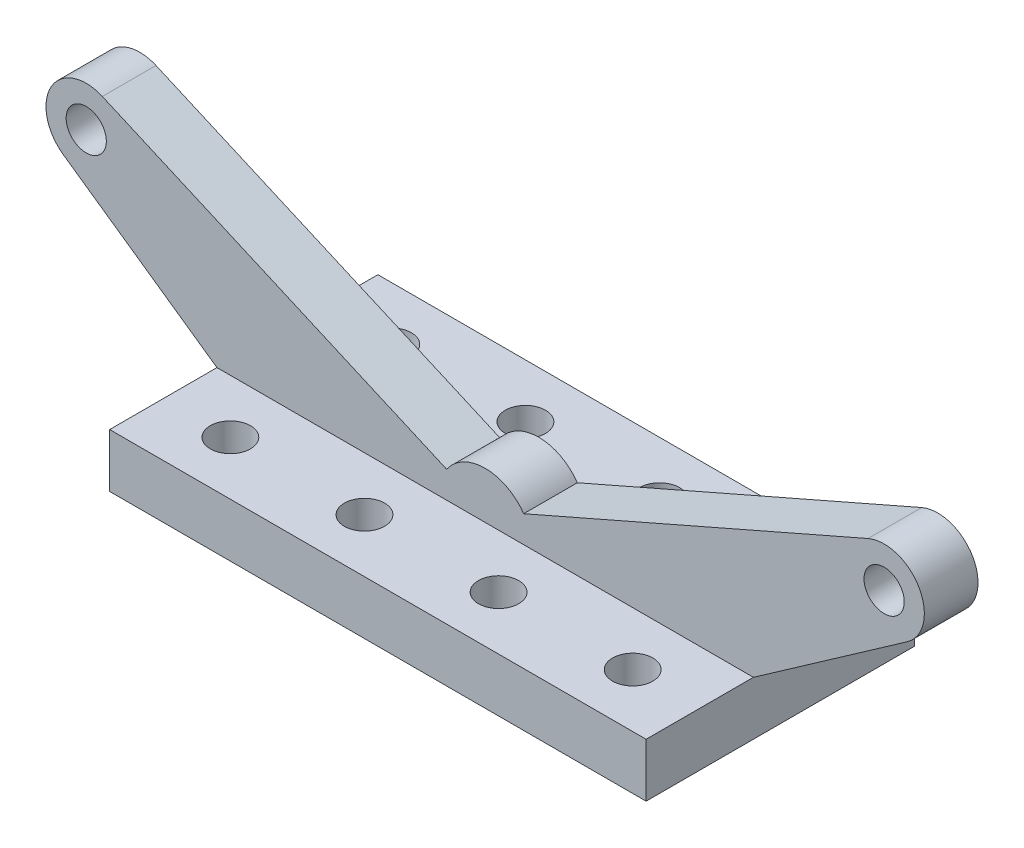
SolidWorks part; units mm, degrees
ref_plane "Front Plane" through (0, 0, 0) normal (0, 0, 1) x (1, 0, 0)
ref_plane "Top Plane" through (0, 0, 0) normal (0, 1, 0) x (1, 0, 0)
ref_plane "Right Plane" through (0, 0, 0) normal (1, 0, 0) x (0, 0, -1)
sketch "Sketch1" plane through (0, 0, 0) normal (0, 1, 0) x (1, 0, 0)
  line L0 (0, 0) -> (-100, 0) construction
  line L1 (-100, -50) -> (100, -50)
  line L2 (-100, -50) -> (-100, 50)
  line L3 (-100, 50) -> (100, 50)
  line L4 (100, -50) -> (100, 50)
  line L5 (-100, -50) -> (100, 50) construction
  line L6 (-100, 50) -> (100, -50) construction
  circle A0 centre (-75, 30) radius 7.5
  circle A1 centre (-75, -30) radius 7.5
  circle A2 centre (-25, 30) radius 7.5
  circle A3 centre (-25, -30) radius 7.5
  circle A4 centre (25, 30) radius 7.5
  circle A5 centre (25, -30) radius 7.5
  circle A6 centre (75, 30) radius 7.5
  circle A7 centre (75, -30) radius 7.5
  point P0 (0, 0)
  dimension "D3" = 15
  dimension "D5" = 60
  dimension "D6" = 4
  dimension "D7" = 50
  dimension "D1" = 200
  dimension "D2" = 100
  dimension "D4" = 25
extrude "Boss-Extrude1" add sketch "Sketch1" along normal blind 20
sketch "Sketch2" plane through (0, 0, 0) normal (0, 0, 1) x (1, 0, 0)
  line L0 (-100, 20) -> (-157.3406, 60.1504)
  line L1 (-100, 20) -> (100, 20) construction
  line L2 (0, 0) -> (0, 87.6863) construction
  line L3 (-157.3406, 60.1504) -> (-138.0598, 87.6863) construction
  line L4 (-142.7228, 86.1792) -> (-14.3614, 30)
  line L5 (157.3406, 60.1504) -> (138.0598, 87.6863) construction
  line L6 (142.7228, 86.1792) -> (14.3614, 30)
  line L7 (100, 20) -> (157.3406, 60.1504)
  line L8 (-100, 20) -> (100, 20)
  arc A0 (-142.7228, 86.1792) -> (-157.3406, 60.1504) centre (-148.737, 72.4376) ccw
  arc A1 (14.3614, 30) -> (-14.3614, 30) centre (0, 20) ccw
  circle A2 centre (-148.737, 72.4376) radius 7.5
  circle A3 centre (148.737, 72.4376) radius 7.5
  arc A4 (142.7228, 86.1792) -> (157.3406, 60.1504) centre (148.737, 72.4376) cw
  point P9 (-14.0639, 30.4143)
  dimension "D3" = 30
  dimension "D4" = 35
  dimension "D5" = 15
  dimension "D1" = 70
  dimension "D2" = 145
  dimension "D6" = 10
extrude "Boss-Extrude2" add sketch "Sketch2" along normal mid plane 20
